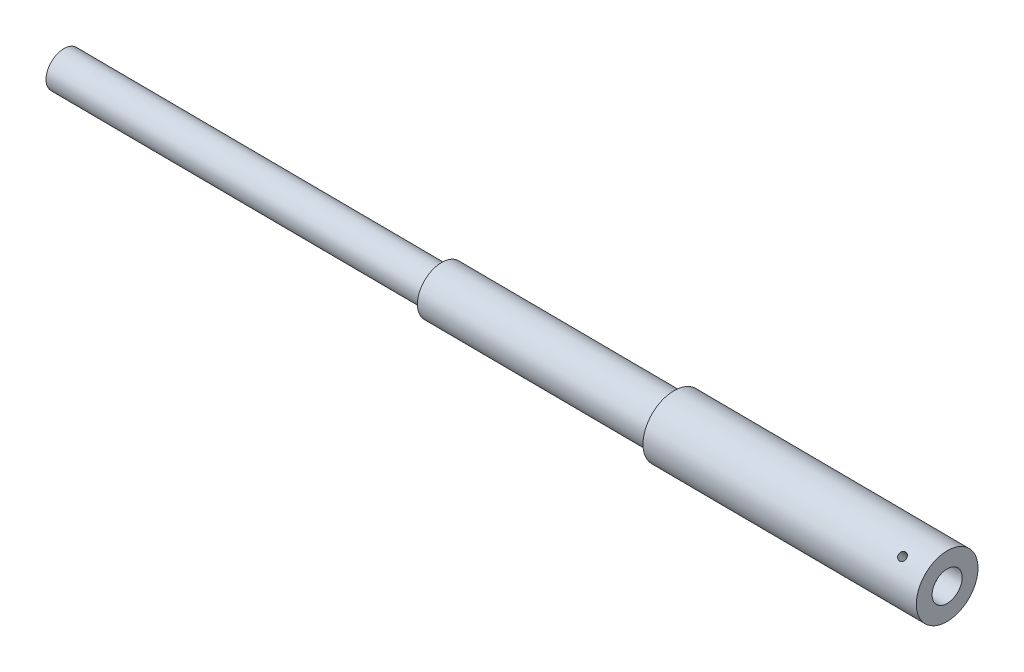
SolidWorks part; units mm, degrees
material "Alloy Steel"
ref_plane "Front Plane" through (0, 0, 0) normal (0, 0, 1) x (1, 0, 0)
ref_plane "Top Plane" through (0, 0, 0) normal (0, 1, 0) x (1, 0, 0)
ref_plane "Right Plane" through (0, 0, 0) normal (1, 0, 0) x (0, 0, -1)
sketch "Sketch1" plane through (0, 0, 0) normal (0, 0, 1) x (1, 0, 0)
  line L0 (-92984.2588, 1591.6625) -> (-78081.161, 1488.3234)
sweep "Sweep1" add path "Sketch1" circular profile diameter 600 parameters "D3"=600
sketch "Sketch18" plane through (0, 0, 0) normal (0, 0, 1) x (1, 0, 0)
  line L0 (-86611.7966, 1547.4754) -> (-78081.161, 1488.3234)
  line L1 (-92984.2588, 1591.6625) -> (-78081.161, 1488.3234) construction
sweep "Sweep2" add path "Sketch18" circular profile diameter 812.8 parameters "D3"=812.8
sketch "Sketch79" plane through (0, 0, 0) normal (0, 0, 1) x (1, 0, 0)
  line L0 (-82692.035, 1520.2955) -> (-78081.161, 1488.3234)
  line L1 (-92984.2588, 1591.6625) -> (-78081.161, 1488.3234) construction
sweep "Sweep3" add path "Sketch79" circular profile diameter 1041.4 parameters "D3"=1041.4
extrude "Cut-Extrude1" cut sketch "Sketch96" against normal mid plane 6000
sketch "Sketch96" plane through (-1329.6493, 16090.3264, -14618.5291) normal (0.0052, 0.7567, 0.6537) x (0.9606, 0.1777, -0.2135)
  circle A1 centre (-79846.4136, 1633.4781) radius 65.5706
sketch "Sketch97" plane through (-92990.8244, 644.8047, 0) normal (-1, 0.0069, 0) x (0, 0, 1)
  circle A0 centre (0, 946.8806) radius 254
  circle A1 centre (0, 946.8806) radius 300 construction
  dimension "D1" = 508
extrude "Cut-Extrude2" cut sketch "Sketch97" against normal through all and the other way through all
